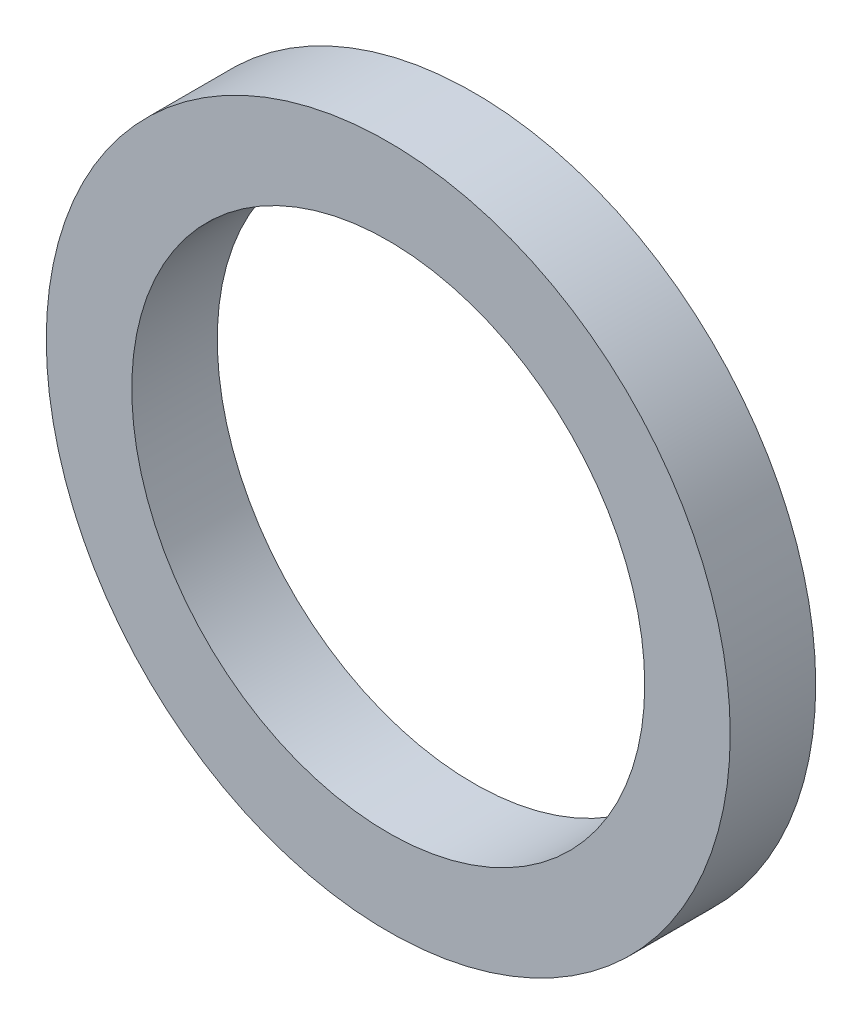
SolidWorks part; units mm, degrees
ref_plane "Plan de face" through (0, 0, 0) normal (0, 0, 1) x (1, 0, 0)
ref_plane "Plan de dessus" through (0, 0, 0) normal (0, 1, 0) x (1, 0, 0)
ref_plane "Plan de droite" through (0, 0, 0) normal (1, 0, 0) x (0, 0, -1)
sketch "Esquisse1" plane through (0, 0, 0) normal (0, 0, 1) x (1, 0, 0)
  circle A0 centre (0, 0) radius 1.5
  circle A1 centre (0, 0) radius 2
  dimension "D1" = 3
  dimension "D2" = 4
extrude "Extrusion1" add sketch "Esquisse1" along normal mid plane 0.5
